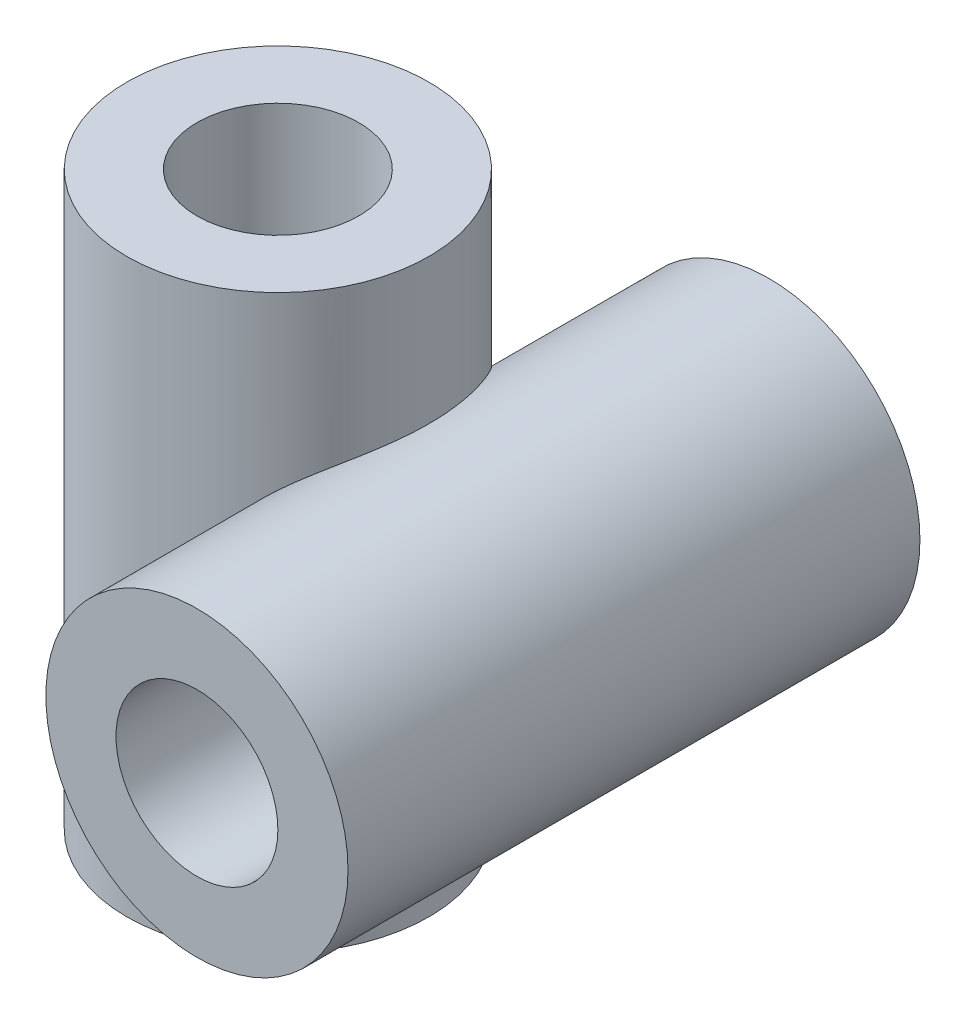
SolidWorks part; units mm, degrees
ref_plane "Front Plane" through (0, 0, 0) normal (0, 0, 1) x (1, 0, 0)
ref_plane "Top Plane" through (0, 0, 0) normal (0, 1, 0) x (1, 0, 0)
ref_plane "Right Plane" through (0, 0, 0) normal (1, 0, 0) x (0, 0, -1)
sketch "Sketch1" plane through (0, 0, 0) normal (0, 0, 1) x (1, 0, 0)
  circle A0 centre (0, 0) radius 15
  circle A1 centre (0, 0) radius 28
  dimension "D1" = 56
  dimension "D2" = 30
extrude "Boss-Extrude1" add sketch "Sketch1" along normal mid plane 106
sketch "Sketch2" plane through (0, 0, 0) normal (0, 1, 0) x (1, 0, 0)
  circle A0 centre (-38, 0) radius 15
  circle A1 centre (-38, 0) radius 28
  dimension "D1" = 56
  dimension "D2" = 30
  dimension "D3" = 38
extrude "Boss-Extrude2" add sketch "Sketch2" along normal mid plane 106
sketch "Sketch3" plane through (0, 53, 0) normal (0, 1, 0) x (1, 0, 0)
  circle A0 centre (-38, 0) radius 15
extrude "Cut-Extrude1" cut sketch "Sketch3" against normal through all
scale "Scale1" scale about centroid uniform scaling yes scale factor 0.3
